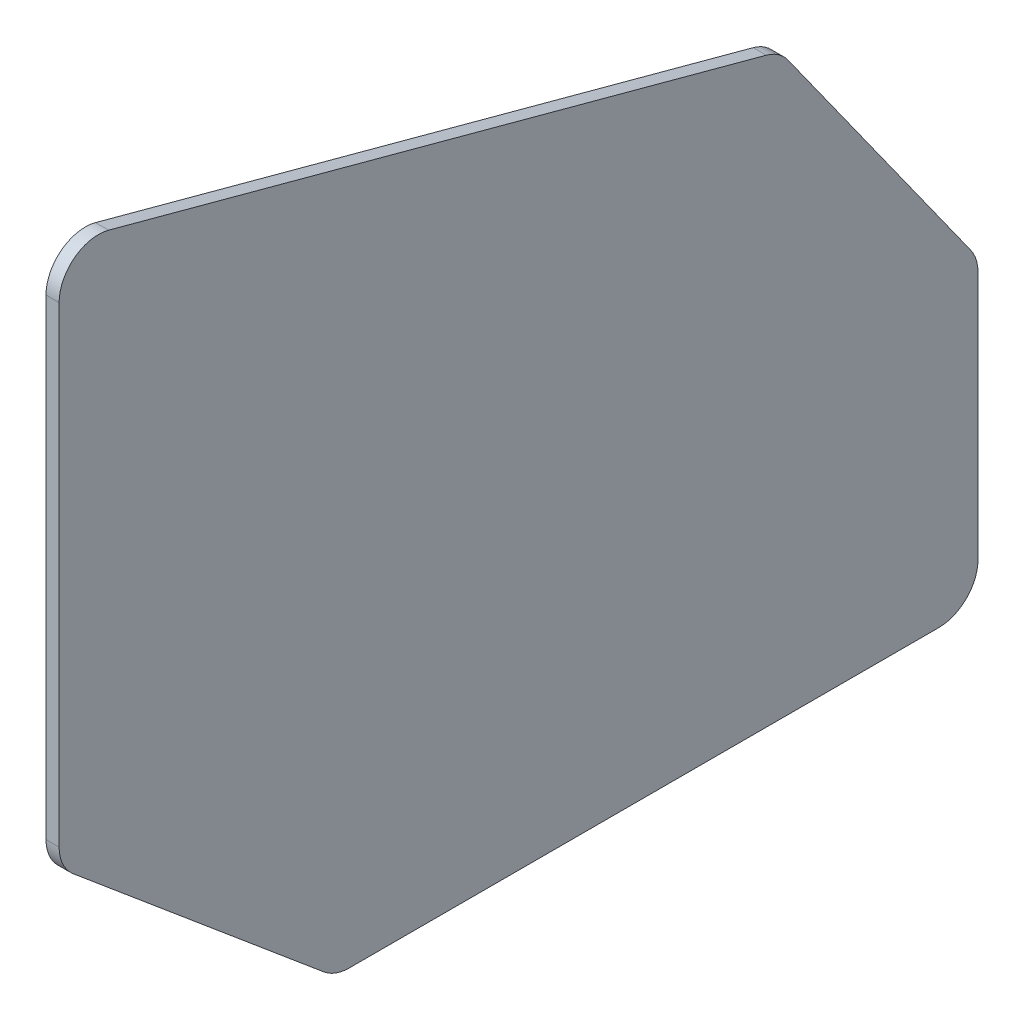
SolidWorks part; units mm, degrees
ref_plane "Front Plane" through (0, 0, 0) normal (0, 0, 1) x (1, 0, 0)
ref_plane "Top Plane" through (0, 0, 0) normal (0, 1, 0) x (1, 0, 0)
ref_plane "Right Plane" through (0, 0, 0) normal (1, 0, 0) x (0, 0, -1)
sketch "Sketch1" plane through (0, 0, 0) normal (1, 0, 0) x (0, 0, -1)
  line L0 (0, -39.1591) -> (0, -399.1591)
  line L1 (0, 303.9402) -> (0, -303.9402) construction
  line L2 (10.7164, -422.1404) -> (202.2275, -582.8373)
  line L3 (221.5111, -589.856) -> (671.5111, -589.856)
  line L4 (701.5111, -559.856) -> (701.5111, -369.856)
  line L5 (695.9285, -352.4263) -> (556.4912, -157.0875)
  line L6 (539.883, -145.5513) -> (37.8091, -10.1933)
  arc A0 (539.883, -145.5513) -> (556.4912, -157.0875) centre (532.0739, -174.5171) cw
  arc A1 (695.9285, -352.4263) -> (701.5111, -369.856) centre (671.5111, -369.856) cw
  arc A2 (701.5111, -559.856) -> (671.5111, -589.856) centre (671.5111, -559.856) cw
  arc A3 (221.5111, -589.856) -> (202.2275, -582.8373) centre (221.5111, -559.856) cw
  arc A4 (10.7164, -422.1404) -> (0, -399.1591) centre (30, -399.1591) cw
  arc A5 (0, -39.1591) -> (37.8091, -10.1933) centre (30, -39.1591) cw
  point P13 (550.2519, -148.3468)
  point P16 (701.5111, -360.2471)
  point P19 (701.5111, -589.856)
  point P22 (210.592, -589.856)
  point P25 (0, -413.1483)
  point P28 (0, 0)
  dimension "D8" = 30
  dimension "D7" = 520
  dimension "D1" = 360
  dimension "D2" = 250
  dimension "D3" = 450
  dimension "D4" = 190
  dimension "D5" = 240
  dimension "D6" = 130
extrude "Boss-Extrude1" add sketch "Sketch1" along normal blind 10
sketch "Sketch2" plane through (10, 0, 0) normal (1, 0, 0) x (0, 0, -1)
  arc A0 (626.3644, -475.9479) -> (646.1337, -523.6267) centre (629.4918, -502.5891) cw
  arc A1 (34.2074, -327.5609) -> (42.3962, -327.5609) centre (38.3018, -332.8216) cw
  arc A2 (66.6989, -215.359) -> (74.2028, -208.2845) centre (70.635, -212.0171) cw
  arc A3 (567.085, -348.1751) -> (577.7555, -393.5269) centre (572.1224, -370.9211) cw
  arc A4 (92.1634, -98.1982) -> (98.8291, -93.9889) centre (95.5389, -96.1611) cw
  arc A5 (331.1797, -194.6855) -> (332.6935, -215.359) centre (331.1807, -205.0776) cw
  spline S0 degree 3 poles (42.3962, -327.5609) (179.9982, -434.6573) (369.4962, -510.0675) (572.4274, -482.2794) (626.3644, -475.9479) knots 0 0 0 0 0.742689 1 1 1 1
  spline S1 degree 3 poles (646.1337, -523.6267) (620.2652, -544.0901) (324.8088, -589.0156) (14.4757, -342.9182) (34.2074, -327.5609) knots 0 0 0 0 0.454281 1 1 1 1
  spline S2 degree 3 poles (66.6989, -215.359) (100.32, -254.9574) (300.3222, -390.0351) (509.6397, -410.5005) (577.7555, -393.5269) knots 0 0 0 0 0.65471 1 1 1 1
  spline S3 degree 3 poles (74.2028, -208.2845) (81.1492, -214.9242) (316.0764, -369.7909) (526.7425, -357.1095) (567.085, -348.1751) knots 0 0 0 0 0.768435 1 1 1 1
  spline S4 degree 3 poles (92.1634, -98.1982) (126.325, -154.8026) (226.9187, -224.5621) (331.9217, -215.4726) (332.6935, -215.359) knots 0 0 0 0 0.645739 1 1 1 1
  spline S5 degree 3 poles (98.8291, -93.9889) (112.6228, -114.8829) (192.7302, -182.1378) (300.1844, -194.6883) (331.1797, -194.6855) knots 0 0 0 0 0.660883 1 1 1 1
  point P20 (0, 0)
  point P22 (248.2679, -175.7269)
  point P23 (98.8291, -93.9889)
  point P24 (243.0715, -179.9398)
  point P27 (330.6114, -186.9064)
  point P29 (0, 0)
  point P30 (230.4501, -179.8851)
  point P31 (0, 0)
  point P32 (331.1807, -194.6855)
  point P33 (255.1755, -205.0776)
  point P34 (92.1634, -98.1982)
  point P35 (74.2028, -208.2845)
  point P36 (258.0782, -212.0171)
  point P37 (0, 0)
  point P38 (0, 0)
  point P39 (29.3498, -331.8519)
  point P40 (34.2074, -327.5609)
  point P41 (0, 0)
sketch "Sketch4" plane through (10, 0, 0) normal (1, 0, 0) x (0, 0, -1)
  arc A2 (646.1337, -523.6267) -> (626.3644, -475.9479) centre (629.4918, -502.5891) ccw
  arc A3 (42.3962, -327.5609) -> (34.2074, -327.5609) centre (38.3018, -332.8216) ccw
  arc A4 (646.1337, -523.6267) -> (626.3644, -475.9479) centre (629.4918, -502.5891) ccw
  arc A5 (42.3962, -327.5609) -> (34.2074, -327.5609) centre (38.3018, -332.8216) ccw
  arc A6 (332.6935, -215.359) -> (331.1797, -194.6855) centre (331.1807, -205.0776) ccw
  arc A7 (98.8291, -93.9889) -> (92.1634, -98.1982) centre (95.5389, -96.1611) ccw
  arc A8 (332.6935, -215.359) -> (331.1797, -194.6855) centre (331.1807, -205.0776) ccw
  arc A9 (98.8291, -93.9889) -> (92.1634, -98.1982) centre (95.5389, -96.1611) ccw
  arc A10 (74.2028, -208.2845) -> (66.6989, -215.359) centre (70.635, -212.0171) ccw
  arc A11 (577.7555, -393.5269) -> (567.085, -348.1751) centre (572.1224, -370.9211) ccw
  arc A12 (74.2028, -208.2845) -> (66.6989, -215.359) centre (70.635, -212.0171) ccw
  arc A13 (577.7555, -393.5269) -> (567.085, -348.1751) centre (572.1224, -370.9211) ccw
  spline S2 degree 3 poles (2464.2398, -2081.6505) (-548.195, 323.3051) (405.5921, -1163.7485) (1230.0919, -121.6341) (-2282.2479, -1142.4189) knots -0.887673 -0.887673 -0.887673 -0.887673 0.545719 2.060312 2.060312 2.060312 2.060312 only from (34.2074, -327.5609) to (646.1337, -523.6267)
  spline S3 degree 3 poles (2226.5612, -2865.6665) (1323.6455, -69.1428) (133.2418, -1164.4427) (-685.8944, 592.4388) (-1408.6195, 2279.9581) knots -1.749601 -1.749601 -1.749601 -1.749601 0.257311 3.507574 3.507574 3.507574 3.507574 only from (626.3644, -475.9479) to (42.3962, -327.5609)
  spline S4 degree 3 poles (34.2074, -327.5609) (14.4757, -342.9182) (324.8088, -589.0156) (620.2652, -544.0901) (646.1337, -523.6267) knots 0 0 0 0 0.545719 1 1 1 1
  spline S5 degree 3 poles (626.3644, -475.9479) (572.4274, -482.2794) (369.4962, -510.0675) (179.9982, -434.6573) (42.3962, -327.5609) knots 0 0 0 0 0.257311 1 1 1 1
  spline S6 degree 3 poles (3002.0956, -225.384) (-363.2568, 729.6054) (66.8164, -586.9794) (599.3431, -71.4658) (-2590.2798, -887.555) knots -2.579265 -2.579265 -2.579265 -2.579265 0.645739 2.241059 2.241059 2.241059 2.241059 only from (92.1634, -98.1982) to (332.6935, -215.359)
  spline S7 degree 3 poles (-2662.3277, -256.9179) (955.8415, 48.1602) (11.379, -589.6416) (-105.524, 428.0104) (2149.1755, -2277.9565) knots -2.348836 -2.348836 -2.348836 -2.348836 0.339117 3.152231 3.152231 3.152231 3.152231 only from (331.1797, -194.6855) to (98.8291, -93.9889)
  spline S8 degree 3 poles (92.1634, -98.1982) (126.325, -154.8026) (226.9187, -224.5621) (331.9217, -215.4726) (332.6935, -215.359) knots 0 0 0 0 0.645739 1 1 1 1
  spline S9 degree 3 poles (331.1797, -194.6855) (300.1844, -194.6883) (192.7302, -182.1378) (112.6228, -114.8829) (98.8291, -93.9889) knots 0 0 0 0 0.339117 1 1 1 1
  spline S10 degree 3 poles (-2402.1254, -319.3194) (1153.6868, 137.1649) (482.2001, -995.3544) (-564.3045, 462.0117) (2387.365, -2117.1897) knots -1.643548 -1.643548 -1.643548 -1.643548 0.231565 2.288063 2.288063 2.288063 2.288063 only from (567.085, -348.1751) to (74.2028, -208.2845)
  spline S11 degree 3 poles (2529.9268, -1920.9073) (-482.2509, 413.9802) (286.5344, -859.8048) (1214.5614, -174.3342) (713.7018, 2525.3071) knots -1.509473 -1.509473 -1.509473 -1.509473 0.65471 2.625093 2.625093 2.625093 2.625093 only from (66.6989, -215.359) to (577.7555, -393.5269)
  spline S12 degree 3 poles (567.085, -348.1751) (526.7425, -357.1095) (316.0764, -369.7909) (81.1492, -214.9242) (74.2028, -208.2845) knots 0 0 0 0 0.231565 1 1 1 1
  spline S13 degree 3 poles (66.6989, -215.359) (100.32, -254.9574) (300.3222, -390.0351) (509.6397, -410.5005) (577.7555, -393.5269) knots 0 0 0 0 0.65471 1 1 1 1
  dimension "D1" = 0
  dimension "D2" = 0
  dimension "D3" = 0
sketch "Sketch5" plane through (0, 0, 0) normal (-1, 0, 0) x (0, 0, 1)
  arc A2 (-331.1797, -194.6855) -> (-332.6935, -215.359) centre (-331.1807, -205.0776) ccw
  arc A3 (-92.1634, -98.1982) -> (-98.8291, -93.9889) centre (-95.5389, -96.1611) ccw
  arc A4 (-331.1797, -194.6855) -> (-332.6935, -215.359) centre (-331.1807, -205.0776) ccw
  arc A5 (-92.1634, -98.1982) -> (-98.8291, -93.9889) centre (-95.5389, -96.1611) ccw
  arc A6 (-626.3644, -475.9479) -> (-646.1337, -523.6267) centre (-629.4918, -502.5891) ccw
  arc A7 (-34.2074, -327.5609) -> (-42.3962, -327.5609) centre (-38.3018, -332.8216) ccw
  arc A8 (-626.3644, -475.9479) -> (-646.1337, -523.6267) centre (-629.4918, -502.5891) ccw
  arc A9 (-34.2074, -327.5609) -> (-42.3962, -327.5609) centre (-38.3018, -332.8216) ccw
  arc A10 (-567.085, -348.1751) -> (-577.7555, -393.5269) centre (-572.1224, -370.9211) ccw
  arc A11 (-66.6989, -215.359) -> (-74.2028, -208.2845) centre (-70.635, -212.0171) ccw
  arc A12 (-567.085, -348.1751) -> (-577.7555, -393.5269) centre (-572.1224, -370.9211) ccw
  arc A13 (-66.6989, -215.359) -> (-74.2028, -208.2845) centre (-70.635, -212.0171) ccw
  spline S2 degree 3 poles (-2149.1751, -2277.956) (105.524, 428.0103) (-11.3786, -589.6373) (-955.8337, 48.1549) (2662.2354, -256.9101) knots -2.152231 -2.152231 -2.152231 -2.152231 0.660883 3.348813 3.348813 3.348813 3.348813 only from (-98.8291, -93.9889) to (-331.1797, -194.6855)
  spline S3 degree 3 poles (2590.3146, -887.5639) (-599.3444, -71.4646) (-66.8186, -586.9793) (363.2541, 729.5969) (-3002.047, -225.3702) knots -1.241065 -1.241065 -1.241065 -1.241065 0.354261 3.57925 3.57925 3.57925 3.57925 only from (-332.6935, -215.359) to (-92.1634, -98.1982)
  spline S4 degree 3 poles (-98.8291, -93.9889) (-112.6228, -114.8829) (-192.7302, -182.1378) (-300.1844, -194.6883) (-331.1797, -194.6855) knots 0 0 0 0 0.660883 1 1 1 1
  spline S5 degree 3 poles (-332.6935, -215.359) (-331.9217, -215.4726) (-226.9187, -224.5621) (-126.325, -154.8026) (-92.1634, -98.1982) knots 0 0 0 0 0.354261 1 1 1 1
  spline S6 degree 3 poles (1408.6303, 2279.9835) (685.8995, 592.4497) (-133.2388, -1164.4477) (-1323.6477, -69.1408) (-2226.5678, -2865.6868) knots -2.50759 -2.50759 -2.50759 -2.50759 0.742689 2.749606 2.749606 2.749606 2.749606 only from (-42.3962, -327.5609) to (-626.3644, -475.9479)
  spline S7 degree 3 poles (2282.3909, -1142.4605) (-1230.1034, -121.6196) (-405.6018, -1163.7551) (548.1881, 323.2943) (-2464.1721, -2081.5964) knots -1.060333 -1.060333 -1.060333 -1.060333 0.454281 1.887662 1.887662 1.887662 1.887662 only from (-646.1337, -523.6267) to (-34.2074, -327.5609)
  spline S8 degree 3 poles (-42.3962, -327.5609) (-179.9982, -434.6573) (-369.4962, -510.0675) (-572.4274, -482.2794) (-626.3644, -475.9479) knots 0 0 0 0 0.742689 1 1 1 1
  spline S9 degree 3 poles (-646.1337, -523.6267) (-620.2652, -544.0901) (-324.8088, -589.0156) (-14.4757, -342.9182) (-34.2074, -327.5609) knots 0 0 0 0 0.454281 1 1 1 1
  spline S10 degree 3 poles (-2387.4004, -2117.2207) (564.3089, 462.0178) (-482.1996, -995.3579) (-1153.6879, 137.1668) (2402.1439, -319.3217) knots -1.288071 -1.288071 -1.288071 -1.288071 0.768435 2.643551 2.643551 2.643551 2.643551 only from (-74.2028, -208.2845) to (-567.085, -348.1751)
  spline S11 degree 3 poles (-713.6874, 2525.3846) (-1214.5699, -174.3279) (-286.5381, -859.8105) (482.2505, 413.9797) (-2529.9233, -1920.9046) knots -1.625111 -1.625111 -1.625111 -1.625111 0.34529 2.509472 2.509472 2.509472 2.509472 only from (-577.7555, -393.5269) to (-66.6989, -215.359)
  spline S12 degree 3 poles (-74.2028, -208.2845) (-81.1492, -214.9242) (-316.0764, -369.7909) (-526.7425, -357.1095) (-567.085, -348.1751) knots 0 0 0 0 0.768435 1 1 1 1
  spline S13 degree 3 poles (-577.7555, -393.5269) (-509.6397, -410.5005) (-300.3222, -390.0351) (-100.32, -254.9574) (-66.6989, -215.359) knots 0 0 0 0 0.34529 1 1 1 1
  dimension "D1" = 0
  dimension "D2" = 0
  dimension "D3" = 0
extrude "Cut-Extrude3" cut sketch "Sketch5" against normal blind 7
